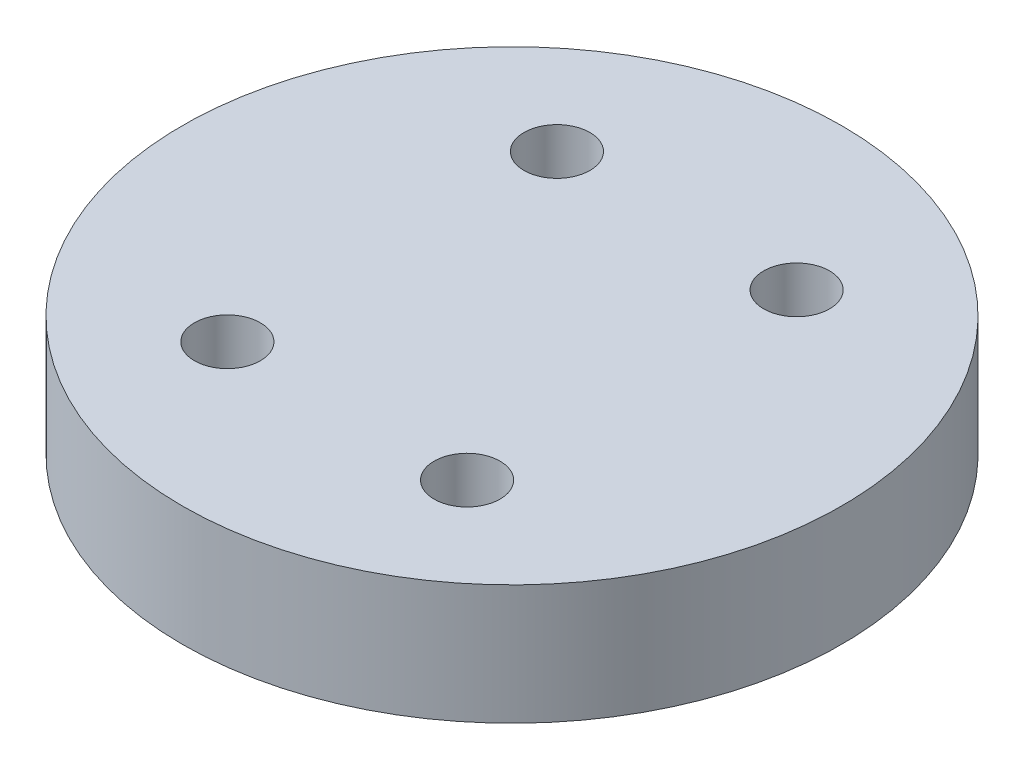
SolidWorks part; units mm, degrees
ref_plane "Front Plane" through (0, 0, 0) normal (0, 0, 1) x (1, 0, 0)
ref_plane "Top Plane" through (0, 0, 0) normal (0, 1, 0) x (1, 0, 0)
ref_plane "Right Plane" through (0, 0, 0) normal (1, 0, 0) x (0, 0, -1)
sketch "Sketch1" plane through (0, 0, 0) normal (0, 1, 0) x (1, 0, 0)
  line L0 (0, 0) -> (0, 68.5524) construction
  line L1 (0, 52.4907) -> (0, -49.3242) construction
  line L2 (10, -13.75) -> (10, 13.75)
  line L3 (10, -13.75) -> (-10, -13.75)
  line L4 (10, 13.75) -> (-10, 13.75)
  line L5 (-10, -13.75) -> (-10, 13.75)
  line L6 (10, -13.75) -> (-10, 13.75) construction
  line L7 (10, 13.75) -> (-10, -13.75) construction
  circle A0 centre (0, 0) radius 27.5
  circle A1 centre (-10, 13.75) radius 2.75
  circle A2 centre (10, 13.75) radius 2.75
  circle A3 centre (10, -13.75) radius 2.75
  circle A4 centre (-10, -13.75) radius 2.75
  dimension "D1" = 55
  dimension "D5" = 5.5
  dimension "D3" = 27.5
  dimension "D4" = 20
extrude "Boss-Extrude1" add sketch "Sketch1" along normal blind 10 contours A0 A4 L5 A1 L4 A2 L2 A3 L3 | A4 L3 A3 L2 A2 L4 A1 L5
equation "\"LOGO_SIZE\"= 40"
equation "\"SECTION_SIZE\"= \"LOGO_SIZE\" / 6"
